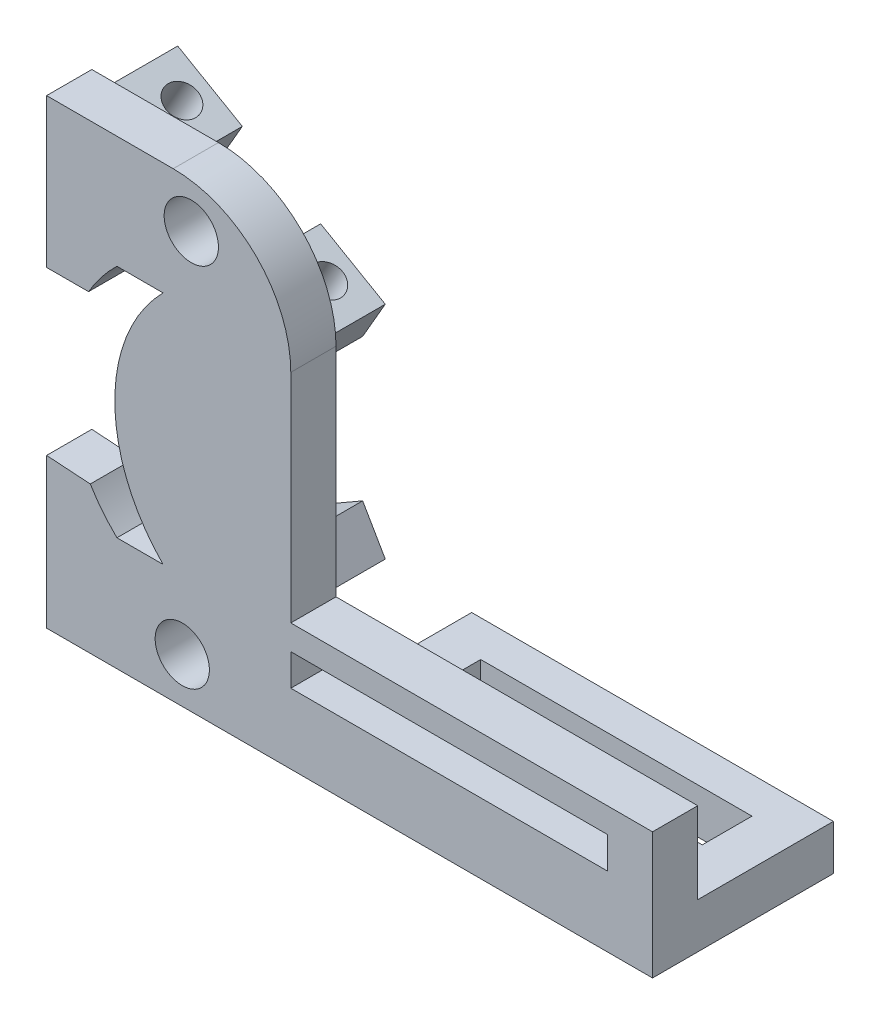
SolidWorks part; units mm, degrees
ref_plane "Alzado" through (0, 0, 0) normal (0, 0, 1) x (1, 0, 0)
ref_plane "Planta" through (0, 0, 0) normal (0, 1, 0) x (1, 0, 0)
ref_plane "Vista lateral" through (0, 0, 0) normal (1, 0, 0) x (0, 0, -1)
sketch "Croquis1" plane through (0, 0, 0) normal (0, 0, 1) x (1, 0, 0)
  line L0 (0, 0) -> (-22.9497, 13.25)
  line L2 (0, 13.25) -> (0, 0) construction
  line L3 (-22.9497, 13.25) -> (-25.4497, 8.9199)
  line L4 (-25.4497, 8.9199) -> (-2.5, -4.3301)
  line L5 (-2.5, -4.3301) -> (0, 0)
  line L6 (-13.9748, 2.2949) -> (-13.9748, -26.7051) construction
  line L7 (-25.4497, -33.3301) -> (-2.5, -20.0801)
  line L8 (-20.4263, -12.2051) -> (-13.9748, -12.2051) construction
  line L9 (-22.9497, -37.6603) -> (-25.4497, -33.3301)
  line L10 (0, -24.4103) -> (-22.9497, -37.6603)
  line L11 (-2.5, -20.0801) -> (0, -24.4103)
  dimension "D1" = 60
  dimension "D2" = 26.5
  dimension "D3" = 5
  dimension "D4" = 29
extrude "Saliente-Extruir1" add sketch "Croquis1" along normal blind 7
sketch "Croquis2" plane through (0, 0, 7) normal (0, 0, 1) x (1, 0, 0)
  line L0 (1.5503, 13.25) -> (-25.4497, 13.25)
  line L5 (1.5503, -37.75) -> (1.5503, 13.25)
  line L7 (1.5503, -37.75) -> (-25.4497, -37.75)
  line L8 (-25.4497, -37.75) -> (-25.4497, 13.25)
  dimension "D1" = 51
  dimension "D2" = 27
extrude "Saliente-Extruir2" add sketch "Croquis2" along normal blind 5
sketch "Croquis3" plane through (0, 0, 7) normal (0, 0, -1) x (-1, 0, 0)
  line L0 (18.6933, -12.2051) -> (21.6933, -12.2051) construction
  line L5 (18.6933, -12.2051) -> (-13.6933, -12.2051) construction
  line L6 (13.9748, 2.2949) -> (13.9748, 2.0269) construction
  line L8 (2.5, -4.3301) -> (2.5, -20.0801) construction
  line L9 (25.4497, 8.9199) -> (2.5, -4.3301) construction
  line L10 (13.5715, 0.7949) -> (16.6715, 0.7949)
  line L16 (13.5715, 0.7949) -> (12.5715, 0.7949)
  line L20 (13.5715, -25.2051) -> (16.6715, -25.2051)
  line L23 (17.6715, -25.2051) -> (16.6715, -25.2051)
  line L24 (13.5715, -25.2051) -> (12.5715, -25.2051)
  line L25 (17.6715, 0.7949) -> (16.6715, 0.7949)
  line L26 (12.5715, -25.2051) -> (12.5715, -12.2051) construction
  line L27 (12.5715, -12.2051) -> (12.5715, 0.7949) construction
  arc A2 (16.6715, 0.7949) -> (16.6715, -25.2051) centre (2.3558, -12.2051) cw construction
  arc A3 (13.5715, 0.7949) -> (13.5715, -25.2051) centre (-0.3657, -12.2051) cw construction
  arc A8 (12.5715, 0.7949) -> (12.5715, -25.2051) centre (-0.591, -12.2051) cw
  arc A9 (17.6715, 0.7949) -> (17.6715, -25.2051) centre (5.2216, -12.2051) cw
  point P15 (2.5, -12.2051)
  dimension "D4" = 1
  dimension "D1" = 3.1
  dimension "D2" = 3
  dimension "D3" = 3.1
  dimension "D5" = 1
  dimension "D6" = 1
  dimension "D7" = 1
  dimension "D8" = 13
extrude "Cortar-Extruir1" cut sketch "Croquis3" against normal up to next
sketch "Croquis4" plane through (-2.5, -4.3301, 0) normal (-0.5, -0.866, 0) x (0.866, -0.5, 0)
  line L0 (-26.5, 3) -> (-22.5, 3) construction
  line L4 (-4, 3) -> (0, 3) construction
  line L5 (-26.5, 7) -> (0, 7) construction
  line L6 (-22.5, 3) -> (-4, 3) construction
  line L7 (0, 7) -> (0, 0) construction
  circle A0 centre (-22.5, 3) radius 1.75
  circle A1 centre (-4, 3) radius 1.75
  dimension "D1" = 3.5
  dimension "D2" = 4
  dimension "D3" = 4
  dimension "D4" = 18.5
extrude "Cortar-Extruir2" cut sketch "Croquis4" against normal up to surface (5 mm away) up to face at (-11.4748, 6.625, 3.5)
sketch "Croquis5" plane through (8.07, -13.9776, 0) normal (-0.5, 0.866, 0) x (0.866, 0.5, 0)
  line L0 (-38.7051, -3) -> (-34.7051, -3) construction
  line L2 (-12.2051, -7) -> (-38.7051, -7) construction
  line L4 (-34.7051, -3) -> (-16.2051, -3) construction
  line L5 (-38.7051, -7) -> (-38.7051, 0) construction
  line L6 (-16.2051, -3) -> (-12.2051, -3) construction
  line L7 (-12.2051, -7) -> (-12.2051, 0) construction
  circle A0 centre (-34.7051, -3) radius 1.75
  circle A1 centre (-16.2051, -3) radius 1.75
  dimension "D2" = 3.5
  dimension "D1" = 4
  dimension "D3" = 4
  dimension "D4" = 18.5
extrude "Cortar-Extruir3" cut sketch "Croquis5" against normal up to next
fillet "Redondeo1" radius 13 1 edges at (1.5503, 13.25, 9.5)
sketch "Croquis6" plane through (0, -37.75, 0) normal (0, -1, 0) x (1, 0, 0)
  line L1 (1.5503, -8) -> (41.5503, -8)
  line L3 (1.5503, 12) -> (41.5503, 12)
  line L4 (41.5503, -8) -> (41.5503, 12)
  line L5 (1.5503, -8) -> (1.5503, 12)
  line L7 (6.5503, 1.5) -> (36.5503, 1.5)
  line L8 (6.5503, 1.5) -> (6.5503, -4)
  line L9 (6.5503, -4) -> (36.5503, -4)
  line L10 (36.5503, 1.5) -> (36.5503, -4)
  line L12 (1.5503, 12) -> (1.5503, 7) construction
  line L14 (-25.4497, 12) -> (1.5503, 12) construction
  point P13 (21.5503, -4)
  point P14 (21.5503, -8)
  dimension "D1" = 20
  dimension "D2" = 40
  dimension "D3" = 5.5
  dimension "D4" = 5
  dimension "D5" = 4
extrude "Saliente-Extruir3" add sketch "Croquis6" against normal blind 5
fillet "Redondeo5" radius 3 1 edges at (1.5503, -35.25, 7)
sketch "Croquis7" plane through (8.07, -13.9776, 0) normal (-0.5, 0.866, 0) x (0.866, 0.5, 0)
  line L0 (-12.2051, 0) -> (-38.7051, 0) construction
  line L1 (-30.4551, 0) -> (-20.4551, 0)
  line L2 (-30.4551, 0) -> (-30.4551, -7)
  line L3 (-30.4551, -7) -> (-20.4551, -7)
  line L4 (-20.4551, 0) -> (-20.4551, -7)
  line L5 (-12.2051, -7) -> (-38.7051, -7) construction
  point P8 (-25.4551, -7)
  point P9 (-25.4551, -7)
  dimension "D1" = 10
extrude "Cortar-Extruir4" cut sketch "Croquis7" against normal up to next
sketch "Croquis8" plane through (-2.5, -4.3301, 0) normal (-0.5, -0.866, 0) x (0.866, -0.5, 0)
  line L0 (-26.5, 7) -> (0, 7) construction
  line L1 (-18.25, 7) -> (-8.25, 7)
  line L2 (-18.25, 7) -> (-18.25, 0)
  line L3 (-18.25, 0) -> (-8.25, 0)
  line L4 (-8.25, 7) -> (-8.25, 0)
  line L5 (-26.5, 0) -> (0, 0) construction
  point P8 (-13.25, 0)
  point P9 (-13.25, 0)
  dimension "D1" = 10
extrude "Cortar-Extruir5" cut sketch "Croquis8" against normal up to next
sketch "Croquis9" plane through (0, 0, 7) normal (0, 0, -1) x (-1, 0, 0)
  line L1 (25.4497, -3.2051) -> (25.4497, -21.2051)
  line L2 (21.8075, -12.2051) -> (25.4497, -12.2051) construction
  line L3 (25.4497, -3.2051) -> (20.81, -3.2051)
  line L4 (25.4497, -21.2051) -> (20.6197, -21.527)
  line L5 (25.4497, 8.9199) -> (25.4497, -33.3301) construction
  arc A2 (17.6715, -25.2051) -> (17.6715, 0.7949) centre (5.2216, -12.2051) ccw construction
  arc A3 (20.6197, -21.527) -> (20.81, -3.2051) centre (5.2216, -12.2051) ccw
  dimension "D1" = 9
extrude "Cortar-Extruir6" cut sketch "Croquis9" against normal up to next
sketch "Croquis10" plane through (1.5503, 0, 0) normal (1, 0, 0) x (0, 0, -1)
  line L0 (-12, -32.75) -> (-12, 0.25) construction
  line L1 (-7, -32.75) -> (-12, -32.75)
  line L2 (-7, -32.75) -> (-7, -23.75)
  line L3 (-7, -23.75) -> (-12, -23.75)
  line L4 (-12, -32.75) -> (-12, -23.75)
  dimension "D1" = 9
extrude "Saliente-Extruir4" add sketch "Croquis10" along normal up to surface (40 mm away) up to face at (41.5503, -35.25, 2)
sketch "Croquis11" plane through (0, 0, 7) normal (0, 0, -1) x (-1, 0, 0)
  line L1 (-41.5503, -32.75) -> (-41.5503, -23.75) construction
  line L2 (-36.5503, -26.5) -> (-1.5503, -26.5)
  line L3 (-36.5503, -26.5) -> (-36.5503, -30)
  line L4 (-36.5503, -30) -> (-1.5503, -30)
  line L5 (-1.5503, -26.5) -> (-1.5503, -30)
  line L6 (-1.5503, -23.75) -> (-1.5503, 0.25) construction
  point P6 (-41.5503, -28.25)
  point P7 (-36.5503, -28.25)
  dimension "D1" = 5
  dimension "D2" = 3.5
extrude "Cortar-Extruir7" cut sketch "Croquis11" against normal up to next
sketch "Croquis12" plane through (0, 0, 7) normal (0, 0, -1) x (-1, 0, 0)
  line L0 (11.4497, 13.25) -> (22.9497, 13.25) construction
  line L1 (-1.5503, -23.75) -> (-1.5503, 0.25) construction
  line L2 (25.4497, -37.75) -> (1.4497, -37.75) construction
  line L5 (25.4497, -33.3301) -> (25.4497, -37.75) construction
  circle A0 centre (10.4497, -32.75) radius 3
  circle A1 centre (9.4497, 8.25) radius 3
  dimension "D1" = 6
  dimension "D2" = 6
  dimension "D3" = 5
  dimension "D4" = 11
  dimension "D5" = 5
  dimension "D6" = 15
extrude "Cortar-Extruir8" cut sketch "Croquis12" against normal up to next
